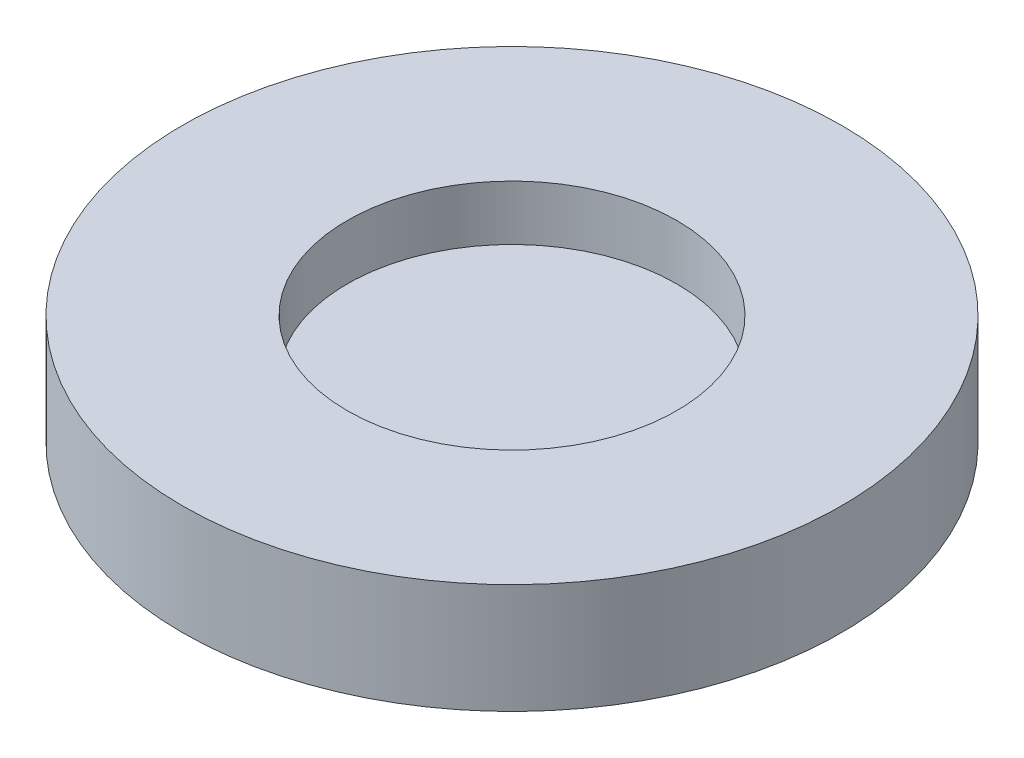
SolidWorks part; units mm, degrees
ref_plane "Plan de face" through (0, 0, 0) normal (0, 0, 1) x (1, 0, 0)
ref_plane "Plan de dessus" through (0, 0, 0) normal (0, 1, 0) x (1, 0, 0)
ref_plane "Plan de droite" through (0, 0, 0) normal (1, 0, 0) x (0, 0, -1)
sketch "Esquisse2" plane through (0, 0, 0) normal (0, 1, 0) x (1, 0, 0)
  circle A0 centre (0, 0) radius 75
  dimension "D1" = 150
extrude "Boss.-Extru.1" add sketch "Esquisse2" along normal blind 25
sketch "Esquisse3" plane through (0, 25, 0) normal (0, 1, 0) x (1, 0, 0)
  circle A0 centre (0, 0) radius 37.5
  dimension "D1" = 75
extrude "Enlèv. mat.-Extru.1" cut sketch "Esquisse3" against normal blind 12.5
